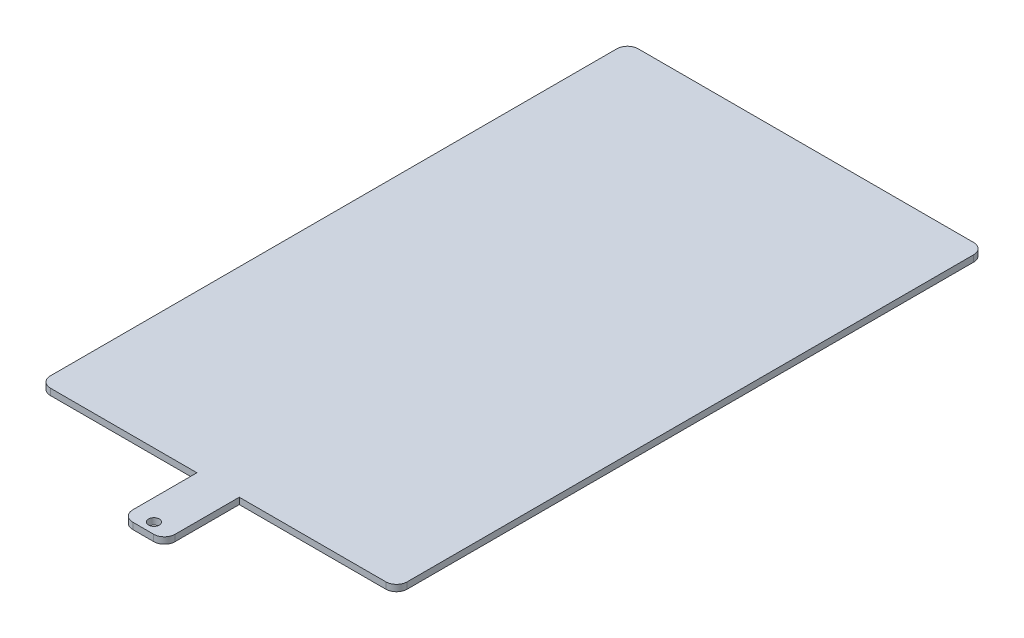
SolidWorks part; units mm, degrees
ref_plane "Front Plane" through (0, 0, 0) normal (0, 0, 1) x (1, 0, 0)
ref_plane "Top Plane" through (0, 0, 0) normal (0, 1, 0) x (1, 0, 0)
ref_plane "Right Plane" through (0, 0, 0) normal (1, 0, 0) x (0, 0, -1)
sketch "Sketch1" plane through (0, 0, 0) normal (0, 1, 0) x (1, 0, 0)
  line L0 (0, 0) -> (73.5, 0)
  line L1 (0, 0) -> (166.8, 0) construction
  line L2 (0, 0) -> (0, 274.8)
  line L3 (0, 274.8) -> (166.8, 274.8)
  line L4 (166.8, 0) -> (166.8, 274.8)
  line L5 (73.5, 0) -> (73.5, -35)
  line L6 (73.5, -35) -> (93.3, -35)
  line L7 (93.3, -35) -> (93.3, 0)
  line L8 (93.3, 0) -> (166.8, 0)
  point P8 (83.4, 0)
  point P10 (83.4, -35)
  dimension "D1" = 166.8
  dimension "D2" = 274.8
  dimension "D3" = 19.8
  dimension "D4" = 35
extrude "Boss-Extrude1" add sketch "Sketch1" along normal blind 3
sketch "Sketch2" plane through (0, 3, 0) normal (0, 1, 0) x (1, 0, 0)
  line L0 (73.5, -35) -> (93.3, -35) construction
  circle A0 centre (83.4, -30) radius 2.5
  point P4 (83.4, -35)
  dimension "D1" = 5
  dimension "D2" = 5
extrude "Cut-Extrude1" cut sketch "Sketch2" against normal blind 5
fillet "Fillet1" radius 5 6 edges at (0, 1.5, 0) (166.8, 1.5, 0) (166.8, 1.5, -274.8) (0, 1.5, -274.8) (93.3, 1.5, 35) (73.5, 1.5, 35)
